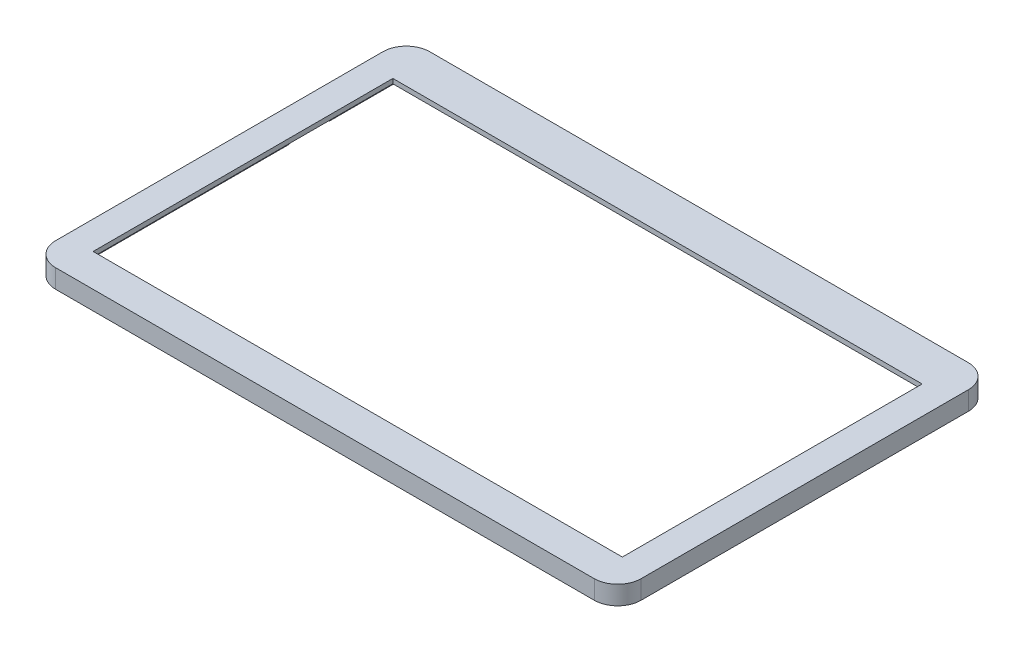
SolidWorks part; units mm, degrees
ref_plane "前视基准面" through (0, 0, 0) normal (0, 0, 1) x (1, 0, 0)
ref_plane "上视基准面" through (0, 0, 0) normal (0, 1, 0) x (1, 0, 0)
ref_plane "右视基准面" through (0, 0, 0) normal (1, 0, 0) x (0, 0, -1)
sketch "草图1" plane through (0, 0, 0) normal (0, 1, 0) x (1, 0, 0)
  line L1 (-99.3407, 63.102) -> (150.6593, 63.102)
  line L2 (-99.3407, 63.102) -> (-99.3407, -92.898)
  line L3 (-99.3407, -92.898) -> (150.6593, -92.898)
  line L4 (150.6593, 63.102) -> (150.6593, -92.898)
  line L5 (-87.3407, 49.102) -> (138.6593, 49.102)
  line L6 (-87.3407, 49.102) -> (-87.3407, -78.898)
  line L7 (-90.3407, 52.102) -> (143.6593, 52.102) construction
  line L8 (-90.3407, 52.102) -> (-90.3407, -85.898) construction
  line L9 (-90.3407, -85.898) -> (143.6593, -85.898) construction
  line L10 (143.6593, 52.102) -> (143.6593, -85.898) construction
  line L11 (-87.3407, -78.898) -> (138.6593, -78.898)
  line L12 (138.6593, 49.102) -> (138.6593, -78.898)
  point P4 (18.2503, -8.9096)
  point P9 (19.2503, -5.5256)
  point P14 (25.6593, -14.898)
  dimension "D1" = 250
  dimension "D2" = 156
  dimension "D3" = 138
  dimension "D4" = 234
  dimension "D5" = 9
  dimension "D6" = 7
  dimension "D7" = 11
  dimension "D8" = 7
  dimension "D9" = 3
  dimension "D10" = 3
  dimension "D11" = 7
  dimension "D12" = 5
extrude "凸台-拉伸1" add sketch "草图1" along normal blind 8
sketch "草图2" plane through (0, 0, 0) normal (0, -1, 0) x (1, 0, 0)
  line L0 (-99.3407, -63.102) -> (-99.3407, 92.898) construction
  line L1 (-93.0907, 82.648) -> (142.4093, 82.648)
  line L2 (-93.0907, 82.648) -> (-93.0907, -56.852)
  line L3 (-93.0907, -56.852) -> (142.4093, -56.852)
  line L4 (142.4093, 82.648) -> (142.4093, -56.852)
  line L5 (-93.0907, 82.648) -> (142.4093, -56.852) construction
  line L6 (-93.0907, -56.852) -> (142.4093, 82.648) construction
  line L7 (-99.3407, 92.898) -> (150.6593, 92.898) construction
  line L13 (150.6593, 92.898) -> (150.6593, -63.102) construction
  line L14 (150.6593, -63.102) -> (-99.3407, -63.102) construction
  point P4 (24.6593, 12.898)
  dimension "D1" = 235.5
  dimension "D2" = 139.5
  dimension "D3" = 6.25
  dimension "D4" = 10.25
  dimension "D5" = 8.25
  dimension "D6" = 6.25
extrude "切除-拉伸3" cut sketch "草图2" against normal blind 6
sketch "草图11" plane through (0, 0, -63.102) normal (0, 0, -1) x (-1, 0, 0)
  line L0 (99.3407, 8) -> (99.3407, 0) construction
  line L1 (-150.6593, 8) -> (99.3407, 8)
  line L2 (-150.6593, 8) -> (-150.6593, 0)
  line L3 (-150.6593, 0) -> (99.3407, 0)
  line L4 (99.3407, 8) -> (99.3407, 0)
  line L5 (-150.6593, 8) -> (99.3407, 0) construction
  line L6 (-150.6593, 0) -> (99.3407, 8) construction
  point P4 (-25.6593, 4)
extrude "凸台-拉伸3" add sketch "草图11" along normal blind 3.75
sketch "草图12" plane through (0, 0, 0) normal (0, -1, 0) x (1, 0, 0)
  line L5 (-89.3407, 92.898) -> (-99.3407, 92.898)
  line L6 (-99.3407, 92.898) -> (-99.3407, 82.898)
  line L7 (-99.3407, -56.852) -> (-99.3407, -66.852)
  line L8 (-99.3407, -66.852) -> (-89.3407, -66.852)
  line L9 (140.6593, -66.852) -> (150.6593, -66.852)
  line L10 (150.6593, -66.852) -> (150.6593, -56.852)
  line L11 (150.6593, 82.898) -> (150.6593, 92.898)
  line L12 (150.6593, 92.898) -> (140.6593, 92.898)
  arc A0 (140.6593, 92.898) -> (150.6593, 82.898) centre (140.6593, 82.898) cw
  arc A1 (150.6593, -56.852) -> (140.6593, -66.852) centre (140.6593, -56.852) cw
  arc A2 (-89.3407, -66.852) -> (-99.3407, -56.852) centre (-89.3407, -56.852) cw
  arc A3 (-99.3407, 82.898) -> (-89.3407, 92.898) centre (-89.3407, 82.898) cw
  point P4 (25.6593, 13.023)
  dimension "D1" = 10
extrude "切除-拉伸4" cut sketch "草图12" against normal blind 10
sketch "草图13" plane through (0, 0, 0) normal (0, -1, 0) x (1, 0, 0)
  line L0 (-99.3407, -56.852) -> (-99.3407, 82.898) construction
  line L1 (-86.3407, 87.898) -> (137.6593, 87.898) construction
  line L2 (-86.3407, 87.898) -> (-86.3407, -61.852) construction
  line L3 (-86.3407, -61.852) -> (137.6593, -61.852) construction
  line L4 (137.6593, 87.898) -> (137.6593, -61.852) construction
  line L6 (150.6593, 82.898) -> (150.6593, -56.852) construction
  line L7 (-89.3407, 92.898) -> (140.6593, 92.898) construction
  line L8 (-93.0907, -56.852) -> (142.4093, -56.852) construction
  circle A0 centre (-86.3407, 87.898) radius 2
  circle A1 centre (137.6593, 87.898) radius 2
  circle A2 centre (137.6593, -61.852) radius 2
  circle A3 centre (-86.3407, -61.852) radius 2
  point P11 (27.5493, 12.6457)
  dimension "D1" = 13
  dimension "D2" = 13
  dimension "D3" = 5
  dimension "D4" = 5
extrude "切除-拉伸5" cut sketch "草图13" against normal blind 6
sketch "草图14" plane through (0, 0, 0) normal (0, -1, 0) x (1, 0, 0)
  line L0 (-99.3407, -56.852) -> (-99.3407, 82.898) construction
  line L1 (-99.3407, -10.502) -> (-93.0907, -10.502)
  line L2 (-99.3407, -10.502) -> (-99.3407, -27.702)
  line L3 (-99.3407, -27.702) -> (-93.0907, -27.702)
  line L4 (-93.0907, -10.502) -> (-93.0907, -27.702)
  line L5 (-93.0907, 82.648) -> (-93.0907, -56.852) construction
  line L7 (140.6593, -66.852) -> (-89.3407, -66.852) construction
  point P8 (-93.0907, -19.102)
  point P9 (-99.3407, -19.102)
  dimension "D1" = 47.75
  dimension "D2" = 17.2
extrude "切除-拉伸6" cut sketch "草图14" against normal blind 1.5
sketch "草图16" plane through (0, 1.5, 0) normal (0, -1, 0) x (1, 0, 0)
  line L6 (-93.0907, -10.502) -> (-99.3407, -10.502) construction
  line L7 (-93.0907, -27.702) -> (-96.9407, -27.702)
  line L8 (-93.0907, -27.702) -> (-93.0907, -10.502)
  line L9 (-93.0907, -10.502) -> (-96.9407, -10.502)
  line L10 (-96.9407, -27.702) -> (-96.9407, -10.502)
  line L11 (-99.3407, -10.502) -> (-99.3407, -27.702) construction
  dimension "D1" = 2.4
extrude "切除-拉伸8" cut sketch "草图16" against normal blind 1.5
